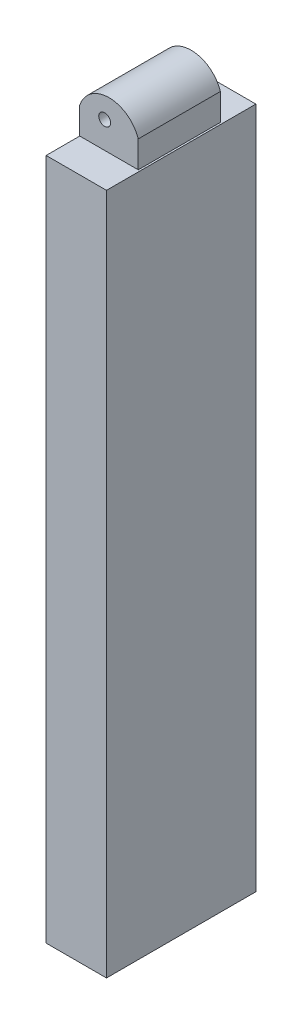
SolidWorks part; units mm, degrees
ref_plane "Front Plane" through (0, 0, 0) normal (1, 0, 0) x (0, 1, 0)
ref_plane "Top Plane" through (0, 0, 0) normal (0, 0, 1) x (0, 1, 0)
ref_plane "Right Plane" through (0, 0, 0) normal (0, 1, 0) x (-1, 0, 0)
sketch "Sketch1" plane through (0, 0, 0) normal (1, 0, 0) x (0, 1, 0)
  line L1 (-54.8, -12) -> (54.8, -12)
  line L2 (-54.8, -12) -> (-54.8, 12)
  line L3 (-54.8, 12) -> (54.8, 12)
  line L4 (54.8, -12) -> (54.8, 12)
  line L5 (-54.8, -12) -> (54.8, 12) construction
  line L6 (-54.8, 12) -> (54.8, -12) construction
  line L7 (44.8, 10) -> (-54.8, 10)
  line L8 (44.8, 10) -> (44.8, -10)
  line L9 (44.8, -10) -> (-54.8, -10)
  line L10 (-54.8, 10) -> (-54.8, -10)
  point P0 (0, 0)
  dimension "D1" = 24
  dimension "D2" = 109.6
  dimension "D3" = 2
  dimension "D4" = 2
  dimension "D5" = 10
extrude "Boss-Extrude1" add sketch "Sketch1" along normal blind 9.7 contours L3 L4 L1 L2
sketch "Sketch3" plane through (0, 54.8, 0) normal (0, 1, 0) x (-1, 0, 0)
  line L1 (-9.4, 6.6) -> (0, 6.6)
  line L2 (-9.4, 6.6) -> (-9.4, -6.6)
  line L3 (-9.4, -6.6) -> (0, -6.6)
  line L4 (0, 6.6) -> (0, -6.6)
  line L5 (0, -12) -> (0, 12) construction
  line L6 (-9.7, -12) -> (0, -12) construction
  line L7 (-9.7, 12) -> (0, 12) construction
  line L9 (-9.7, -12) -> (-9.7, 12) construction
  dimension "D1" = 5.4
  dimension "D2" = 5.4
  dimension "D3" = 0.3
  dimension "D4" = 13.2
extrude "Boss-Extrude2" add sketch "Sketch3" along normal blind 8
sketch "Sketch4" plane through (0, 0, 6.6) normal (0, 0, 1) x (1, 0, 0)
  line L0 (4, 55.1) -> (4, 63.1) construction
  line L9 (0, 54.8) -> (8, 54.8) construction
  line L10 (9.7, 54.8) -> (0, 54.8) construction
  line L14 (0, 54.8) -> (0, 62.5) construction
  line L15 (0, 62.5) -> (8, 62.5) construction
  line L16 (8, 62.5) -> (8, 54.8) construction
  line L18 (-1.4, 59.1) -> (9.4, 59.1) construction
  line L19 (9.4, 62.8) -> (9.4, 54.8) construction
  line L20 (0, 55.1) -> (8, 55.1) construction
  circle A1 centre (4, 59.1) radius 0.95
  arc A3 (0, 59.1) -> (9.4, 59.1) centre (4.7, 57.5515) cw
  point P10 (4, 59.1)
  point P16 (4.0501, 56.2705)
  point P22 (3.9756, 55.5996)
  point P25 (8, 55.1)
  point P26 (4, 55.1)
  dimension "D2" = 1.9
  dimension "D1" = 8
  dimension "D3" = 8
  dimension "D4" = 7.7
  dimension "D5" = 0.3
extrude "Cut-Extrude1" cut sketch "Sketch4" against normal through all
